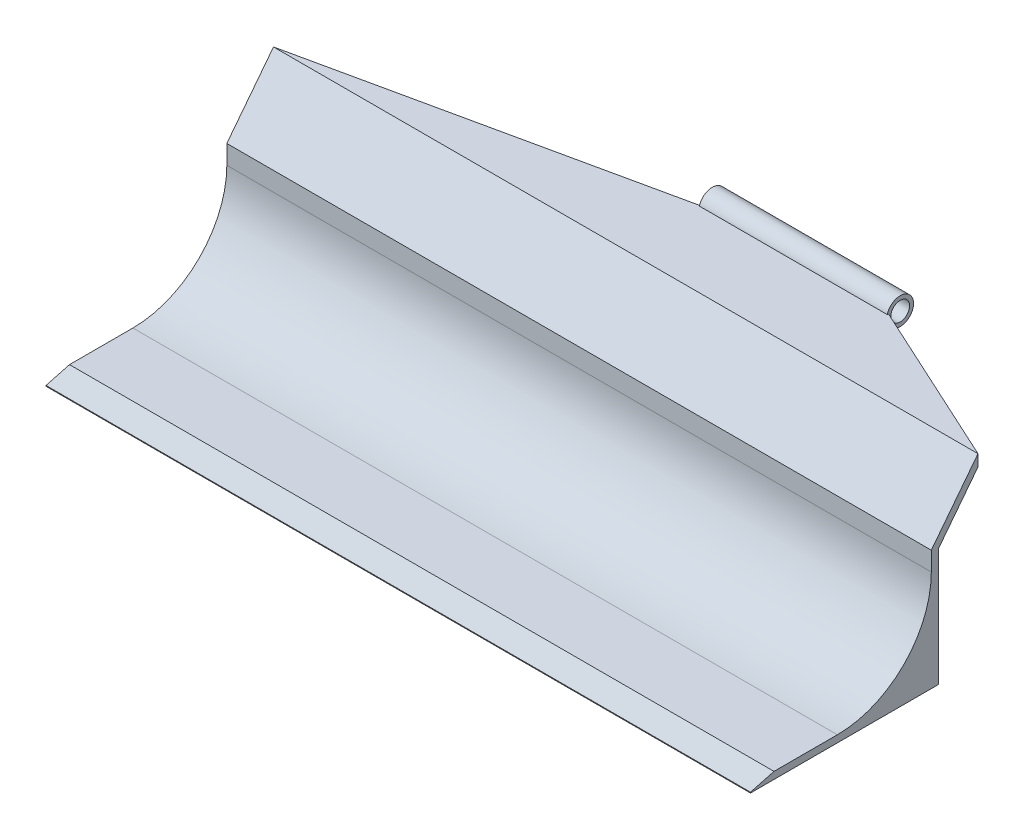
SolidWorks part; units mm, degrees
ref_plane "Front Plane" through (0, 0, 0) normal (0, 0, 1) x (1, 0, 0)
ref_plane "Top Plane" through (0, 0, 0) normal (0, 1, 0) x (1, 0, 0)
ref_plane "Right Plane" through (0, 0, 0) normal (1, 0, 0) x (0, 0, -1)
sketch "Sketch1" plane through (0, 0, 0) normal (1, 0, 0) x (0, 0, -1)
  line L0 (84.9224, -7.246) -> (84.9224, -55.3162)
  line L3 (7.9224, -58.3162) -> (87.9224, -58.3162)
  line L4 (87.9224, -8.2727) -> (87.9224, -58.3162)
  line L5 (7.9224, -55.3162) -> (84.9224, -55.3162)
  line L6 (7.9224, -55.3162) -> (7.9224, -58.3162)
  line L8 (87.9224, -8.2727) -> (106.2735, 15.3974)
  line L9 (106.2735, 15.3974) -> (137.2896, 15.3974)
  line L10 (84.9224, -7.246) -> (104.8034, 18.3974)
  line L11 (104.8034, 18.3974) -> (137.2896, 18.3974)
  line L12 (85.5515, -6.4346) -> (104.8034, 18.3974) construction
  line L13 (84.9224, 26.6838) -> (84.9224, -55.3162) construction
  line L14 (87.9224, 26.6838) -> (87.9224, -58.3162) construction
  line L15 (137.2896, 18.3974) -> (137.2896, 15.3974)
  dimension "D2" = 80
  dimension "D3" = 3
  dimension "D4" = 3
extrude "Boss-Extrude1" add sketch "Sketch1" along normal blind 300
fillet "Fillet1" radius 40 1 edges at (150, -55.3162, -84.9224)
chamfer "Chamfer1" distance 10 angle 15 1 edges at (150, -55.3162, -7.9224)
sketch "Sketch2" plane through (0, 0, 0) normal (0, 1, 0) x (1, 0, 0)
  line L0 (229.3644, 137.2896) -> (300, 104.8034)
  line L1 (300, 137.2896) -> (0, 137.2896) construction
  line L2 (150, 137.2896) -> (0, 104.8034)
  line L3 (300, 104.8034) -> (0, 104.8034) construction
  line L4 (0, 104.8034) -> (-27.4221, 146.5592)
  line L5 (-27.4221, 146.5592) -> (121.1402, 173.1233)
  line L6 (121.1402, 173.1233) -> (150, 137.2896)
  line L7 (229.3644, 137.2896) -> (246.4179, 173.1233)
  line L8 (246.4179, 173.1233) -> (319.8792, 155.2065)
  line L9 (319.8792, 155.2065) -> (319.8792, 121.0465)
  line L10 (319.8792, 121.0465) -> (300, 104.8034)
extrude "Cut-Extrude1" cut sketch "Sketch2" against normal through all both and the other way through all
sketch "Sketch4" plane through (0, 0, -137.2896) normal (0, 0, -1) x (-1, 0, 0)
  line L0 (-296.8034, 15.3974) -> (-6.7881, 15.3974) construction
  line L1 (-229.3644, 18.3974) -> (-150, 18.3974)
  line L2 (-229.3644, 18.3974) -> (-229.3644, 15.3974)
  line L3 (-229.3644, 15.3974) -> (-150, 15.3974)
  line L4 (-150, 18.3974) -> (-150, 15.3974)
  line L5 (-229.3644, 15.3974) -> (-150, 15.3974) construction
extrude "Boss-Extrude2" add sketch "Sketch4" along normal blind 10
sketch "Sketch5" plane through (229.3644, 0, 0) normal (1, 0, 0) x (0, 0, -1)
  circle A0 centre (142.2896, 16.8974) radius 5.7042
  circle A1 centre (142.2896, 16.8974) radius 4
  dimension "D1" = 8
extrude "Boss-Extrude3" add sketch "Sketch5" against normal blind 80
sketch "Sketch7" plane through (229.3644, 0, 0) normal (1, 0, 0) x (0, 0, -1)
  circle A0 centre (142.2896, 16.8974) radius 4
extrude "Cut-Extrude2" cut sketch "Sketch7" against normal blind 80
